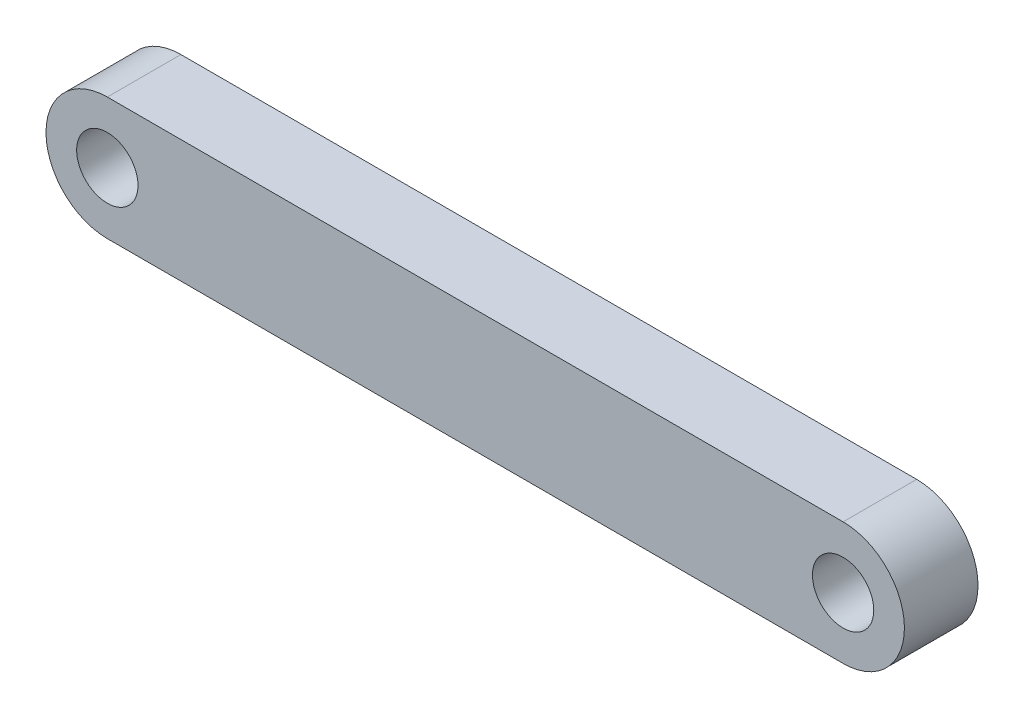
SolidWorks part; units mm, degrees
ref_plane "Front Plane" through (0, 0, 0) normal (0, 0, 1) x (1, 0, 0)
ref_plane "Top Plane" through (0, 0, 0) normal (0, 1, 0) x (1, 0, 0)
ref_plane "Right Plane" through (0, 0, 0) normal (1, 0, 0) x (0, 0, -1)
sketch "Sketch1" plane through (0, 0, 0) normal (0, 0, 1) x (1, 0, 0)
  line L0 (-30, 0) -> (30, 0)
  line L1 (-30, 5) -> (30, 5)
  line L2 (-30, -5) -> (30, -5)
  arc A0 (-30, 5) -> (-30, -5) centre (-30, 0) ccw
  arc A1 (30, -5) -> (30, 5) centre (30, 0) ccw
  circle A2 centre (-30, 0) radius 2.5
  circle A3 centre (30, 0) radius 2.5
  point P4 (0, 0)
  dimension "D2" = 10
  dimension "D3" = 10
  dimension "D4" = 5
  dimension "D5" = 5
  dimension "D1" = 60
extrude "Boss-Extrude1" add sketch "Sketch1" along normal mid plane 6
